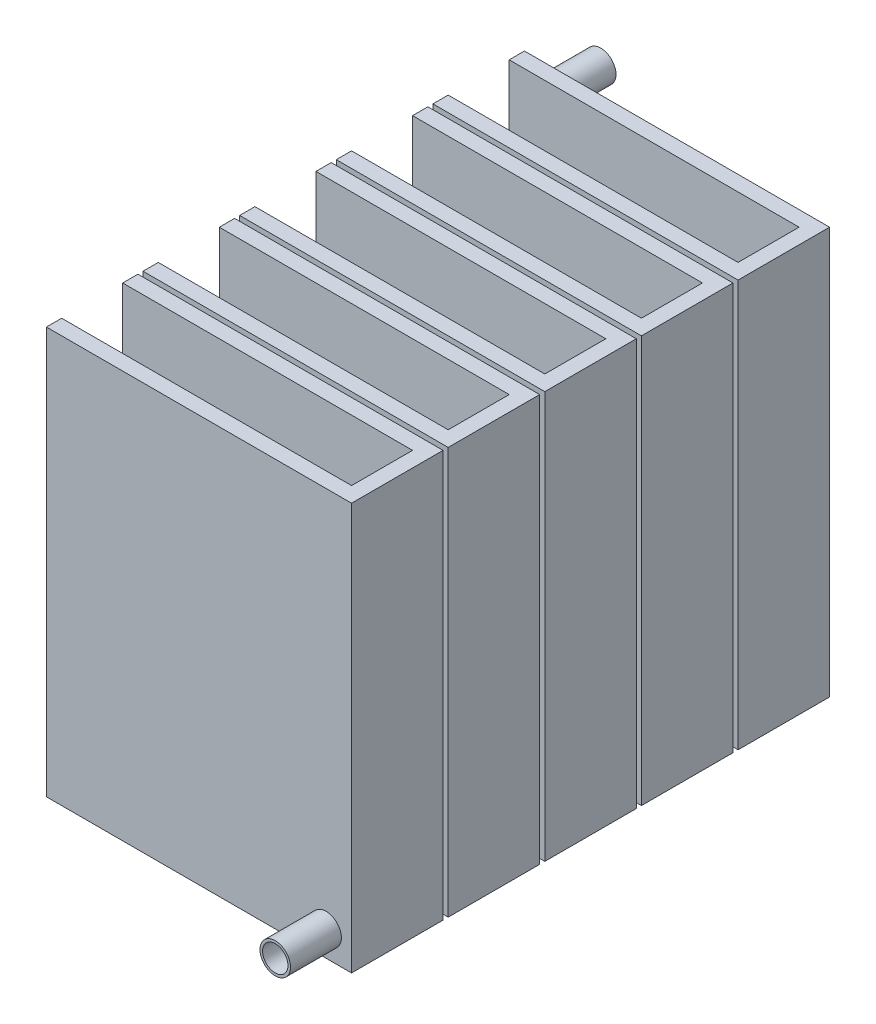
SolidWorks part; units mm, degrees
ref_plane "前视基准面" through (0, 0, 0) normal (0, 0, 1) x (1, 0, 0)
ref_plane "上视基准面" through (0, 0, 0) normal (0, 1, 0) x (1, 0, 0)
ref_plane "右视基准面" through (0, 0, 0) normal (1, 0, 0) x (0, 0, -1)
sketch "草图1" plane through (0, 0, 0) normal (0, 0, 1) x (1, 0, 0)
  line L1 (-30, 40) -> (30, 40)
  line L2 (-30, 40) -> (-30, -40)
  line L3 (-30, -40) -> (30, -40)
  line L4 (30, 40) -> (30, -40)
  line L5 (-30, 40) -> (30, -40) construction
  line L6 (-30, -40) -> (30, 40) construction
  point P0 (0, 0)
  dimension "D1" = 60
  dimension "D2" = 80
extrude "凸台-拉伸1" add sketch "草图1" along normal blind 3
ref_plane "基准面1" through (0, 0, -12) normal (0, 0, -1) x (-1, 0, 0)
sketch "草图2" plane through (0, 0, -12) normal (0, 0, -1) x (-1, 0, 0)
  line L1 (-30, 40) -> (30, 40)
  line L2 (-30, 40) -> (-30, -40)
  line L3 (-30, -40) -> (30, -40)
  line L4 (30, 40) -> (30, -40)
  line L5 (-30, 40) -> (30, -40) construction
  line L6 (-30, -40) -> (30, 40) construction
  point P0 (0, 0)
extrude "凸台-拉伸2" add sketch "草图2" along normal blind 3 separate body
sketch "草图4" plane through (0, 0, 3) normal (0, 0, 1) x (1, 0, 0)
  line L0 (30, -40) -> (30, 40) construction
  line L1 (-30, -40) -> (30, -40) construction
  circle A0 centre (25, -35) radius 3
  dimension "D1" = 6
  dimension "D2" = 5
  dimension "D3" = 5
extrude "凸台-拉伸5" add sketch "草图4" along normal blind 10 contours A0
sketch "草图5" plane through (0, 0, 0) normal (0, 0, -1) x (-1, 0, 0)
  line L0 (-30, 40) -> (-30, -40) construction
  line L1 (-30, -40) -> (30, -40) construction
  circle A0 centre (-25, -35) radius 3
  dimension "D1" = 6
  dimension "D2" = 5
  dimension "D3" = 5
sketch "草图6" plane through (0, 0, -15) normal (0, 0, -1) x (-1, 0, 0)
  line L0 (30, 40) -> (-30, 40) construction
  line L1 (30, -40) -> (30, 40) construction
  circle A0 centre (25, 35) radius 3
  dimension "D1" = 6
  dimension "D2" = 5
  dimension "D3" = 5
extrude "凸台-拉伸7" add sketch "草图6" along normal blind 1
ref_plane "基准面3" through (0, 0, -16) normal (0, 0, -1) x (-1, 0, 0)
sketch "草图7" plane through (0, 0, -16) normal (0, 0, -1) x (-1, 0, 0)
  line L1 (-30, 40) -> (30, 40)
  line L2 (-30, 40) -> (-30, -40)
  line L3 (-30, -40) -> (30, -40)
  line L4 (30, 40) -> (30, -40)
  line L5 (-30, 40) -> (30, -40) construction
  line L6 (-30, -40) -> (30, 40) construction
  point P0 (0, 0)
extrude "凸台-拉伸8" add sketch "草图7" along normal blind 3
sketch "草图10" plane through (0, 0, -12) normal (0, 0, 1) x (1, 0, 0)
  line L0 (-30, -40) -> (30, -40) construction
  line L1 (30, 40) -> (27, 40)
  line L2 (30, 40) -> (30, -40)
  line L3 (30, -40) -> (27, -40)
  line L4 (27, 40) -> (27, -40)
  dimension "D1" = 3
extrude "凸台-拉伸11" add sketch "草图10" along normal blind 12
ref_plane "基准面4" through (0, 0, -31) normal (0, 0, -1) x (-1, 0, 0)
sketch "草图11" plane through (0, 0, -31) normal (0, 0, -1) x (-1, 0, 0)
  line L1 (-30, 40) -> (30, 40)
  line L2 (-30, 40) -> (-30, -40)
  line L3 (-30, -40) -> (30, -40)
  line L4 (30, 40) -> (30, -40)
  line L5 (-30, 40) -> (30, -40) construction
  line L6 (-30, -40) -> (30, 40) construction
  point P0 (0, 0)
extrude "凸台-拉伸12" add sketch "草图11" along normal blind 3 separate body
sketch "草图12" plane through (0, 0, -31) normal (0, 0, -1) x (-1, 0, 0)
  line L0 (30, -40) -> (-30, -40) construction
  line L1 (-30, 40) -> (-27, 40)
  line L2 (-30, 40) -> (-30, -40)
  line L3 (-30, -40) -> (-27, -40)
  line L4 (-27, 40) -> (-27, -40)
  dimension "D1" = 3
extrude "凸台-拉伸13" add sketch "草图12" against normal blind 12
sketch "草图13" plane through (0, 0, -34) normal (0, 0, -1) x (-1, 0, 0)
  circle A0 centre (-25, -35) radius 3
extrude "凸台-拉伸14" add sketch "草图13" along normal blind 1
sketch "草图14" plane through (0, 0, -35) normal (0, 0, -1) x (-1, 0, 0)
  line L1 (-30, 40) -> (30, 40)
  line L2 (-30, 40) -> (-30, -40)
  line L3 (-30, -40) -> (30, -40)
  line L4 (30, 40) -> (30, -40)
  line L5 (-30, 40) -> (30, -40) construction
  line L6 (-30, -40) -> (30, 40) construction
  point P0 (0, 0)
extrude "凸台-拉伸15" add sketch "草图14" along normal blind 3
sketch "草图16" plane through (0, 0, -38) normal (0, 0, -1) x (-1, 0, 0)
  line L0 (-30, -40) -> (30, -40) construction
  line L1 (-30, 40) -> (-27, 40)
  line L2 (-30, 40) -> (-30, -40)
  line L3 (-30, -40) -> (-27, -40)
  line L4 (-27, 40) -> (-27, -40)
  dimension "D1" = 3
extrude "凸台-拉伸16" add sketch "草图16" along normal blind 12
sketch "草图18" plane through (0, 0, -50) normal (0, 0, -1) x (-1, 0, 0)
  line L0 (-27, -40) -> (30, -40) construction
  line L1 (-30, 40) -> (30, 40)
  line L2 (-30, 40) -> (-30, -40)
  line L3 (-30, -40) -> (30, -40)
  line L4 (30, 40) -> (30, -40)
  line L5 (-30, 40) -> (30, -40) construction
  line L6 (-30, -40) -> (30, 40) construction
  point P0 (0, 0)
extrude "凸台-拉伸17" add sketch "草图18" along normal blind 3
sketch "草图20" plane through (0, 0, -53) normal (0, 0, -1) x (-1, 0, 0)
  line L0 (30, -40) -> (30, 40) construction
  line L1 (30, 40) -> (-30, 40) construction
  circle A0 centre (25, 35) radius 3
  dimension "D1" = 6
  dimension "D2" = 5
  dimension "D3" = 5
extrude "凸台-拉伸18" add sketch "草图20" along normal blind 1
sketch "草图21" plane through (0, 0, -54) normal (0, 0, -1) x (-1, 0, 0)
  line L1 (-30, 40) -> (30, 40)
  line L2 (-30, 40) -> (-30, -40)
  line L3 (-30, -40) -> (30, -40)
  line L4 (30, 40) -> (30, -40)
  line L5 (-30, 40) -> (30, -40) construction
  line L6 (-30, -40) -> (30, 40) construction
  point P0 (0, 0)
extrude "凸台-拉伸19" add sketch "草图21" along normal blind 3
sketch "草图22" plane through (0, 0, -57) normal (0, 0, -1) x (-1, 0, 0)
  line L0 (-30, -40) -> (30, -40) construction
  line L1 (-30, 40) -> (-27, 40)
  line L2 (-30, 40) -> (-30, -40)
  line L3 (-30, -40) -> (-27, -40)
  line L4 (-27, 40) -> (-27, -40)
  dimension "D1" = 3
extrude "凸台-拉伸20" add sketch "草图22" along normal blind 12
sketch "草图23" plane through (0, 0, -69) normal (0, 0, -1) x (-1, 0, 0)
  line L1 (-30, 40) -> (30, 40)
  line L2 (-30, 40) -> (-30, -40)
  line L3 (-30, -40) -> (30, -40)
  line L4 (30, 40) -> (30, -40)
  line L5 (-30, 40) -> (30, -40) construction
  line L6 (-30, -40) -> (30, 40) construction
  point P0 (0, 0)
extrude "凸台-拉伸21" add sketch "草图23" along normal blind 3
sketch "草图24" plane through (0, 0, -72) normal (0, 0, -1) x (-1, 0, 0)
  circle A0 centre (-25, -35) radius 3
extrude "凸台-拉伸22" add sketch "草图24" along normal blind 1
sketch "草图25" plane through (0, 0, -73) normal (0, 0, -1) x (-1, 0, 0)
  line L1 (-30, 40) -> (30, 40)
  line L2 (-30, 40) -> (-30, -40)
  line L3 (-30, -40) -> (30, -40)
  line L4 (30, 40) -> (30, -40)
  line L5 (-30, 40) -> (30, -40) construction
  line L6 (-30, -40) -> (30, 40) construction
  point P0 (0, 0)
extrude "凸台-拉伸23" add sketch "草图25" along normal blind 3
sketch "草图26" plane through (0, 0, -76) normal (0, 0, -1) x (-1, 0, 0)
  line L0 (-30, -40) -> (30, -40) construction
  line L1 (-30, 40) -> (-27, 40)
  line L2 (-30, 40) -> (-30, -40)
  line L3 (-30, -40) -> (-27, -40)
  line L4 (-27, 40) -> (-27, -40)
  dimension "D1" = 3
extrude "凸台-拉伸24" add sketch "草图26" along normal blind 12
sketch "草图28" plane through (0, 0, -88) normal (0, 0, -1) x (-1, 0, 0)
  line L1 (-30, 40) -> (30, 40)
  line L2 (-30, 40) -> (-30, -40)
  line L3 (-30, -40) -> (30, -40)
  line L4 (30, 40) -> (30, -40)
  line L5 (-30, 40) -> (30, -40) construction
  line L6 (-30, -40) -> (30, 40) construction
  point P0 (0, 0)
extrude "凸台-拉伸25" add sketch "草图28" along normal blind 3
sketch "草图29" plane through (0, 0, -91) normal (0, 0, -1) x (-1, 0, 0)
  line L0 (30, -40) -> (30, 40) construction
  line L1 (30, 40) -> (-30, 40) construction
  circle A0 centre (25, 35) radius 3
  dimension "D1" = 6
  dimension "D2" = 5
  dimension "D3" = 5
extrude "凸台-拉伸26" add sketch "草图29" along normal blind 10
shell "抽壳1" thickness 0.5
shell "抽壳2" thickness 0.5
